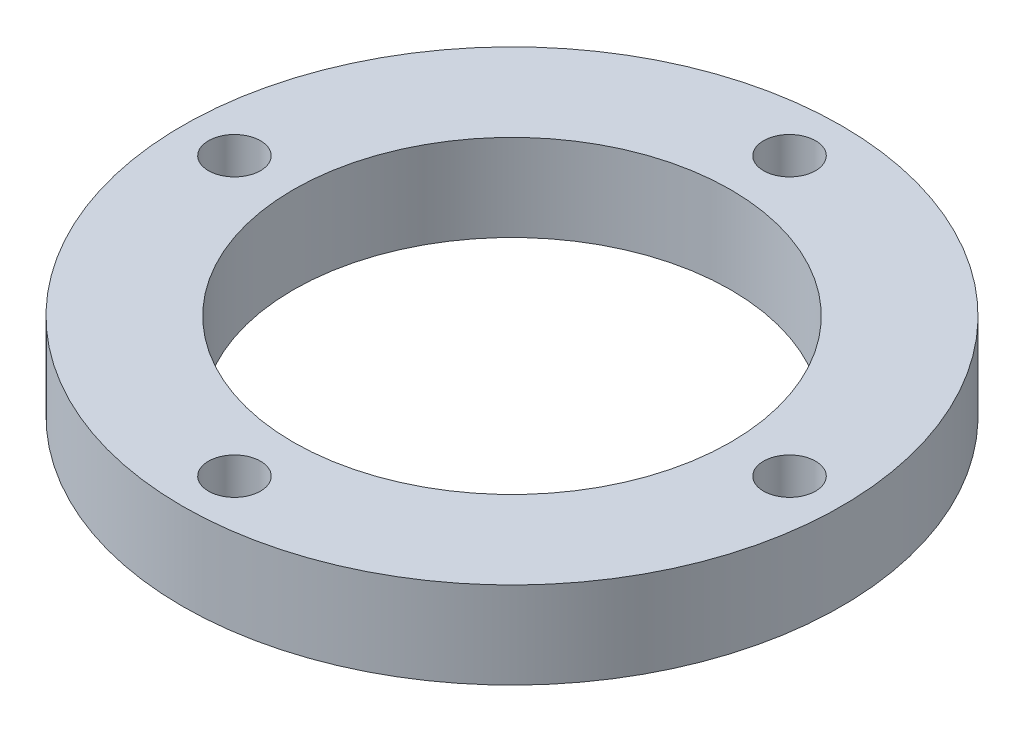
SolidWorks part; units mm, degrees
ref_plane "Спереди" through (0, 0, 0) normal (0, 0, 1) x (1, 0, 0)
ref_plane "Сверху" through (0, 0, 0) normal (0, 1, 0) x (1, 0, 0)
ref_plane "Справа" through (0, 0, 0) normal (1, 0, 0) x (0, 0, -1)
sketch "Эскиз1" plane through (0, 0, 0) normal (0, 1, 0) x (1, 0, 0)
  circle A0 centre (0, 0) radius 19
  circle A1 centre (0, 0) radius 12.61
extrude "Вытянуть1" add sketch "Эскиз1" along normal blind 5
sketch "Эскиз2" plane through (0, 5, 0) normal (0, 1, 0) x (1, 0, 0)
  circle A0 centre (0, 16) radius 1.5
  circle A1 centre (16, 0) radius 1.5
  circle A2 centre (0, -16) radius 1.5
  circle A3 centre (-16, 0) radius 1.5
  dimension "D1" = 16
extrude "Вытянуть2" cut sketch "Эскиз2" against normal blind 5
